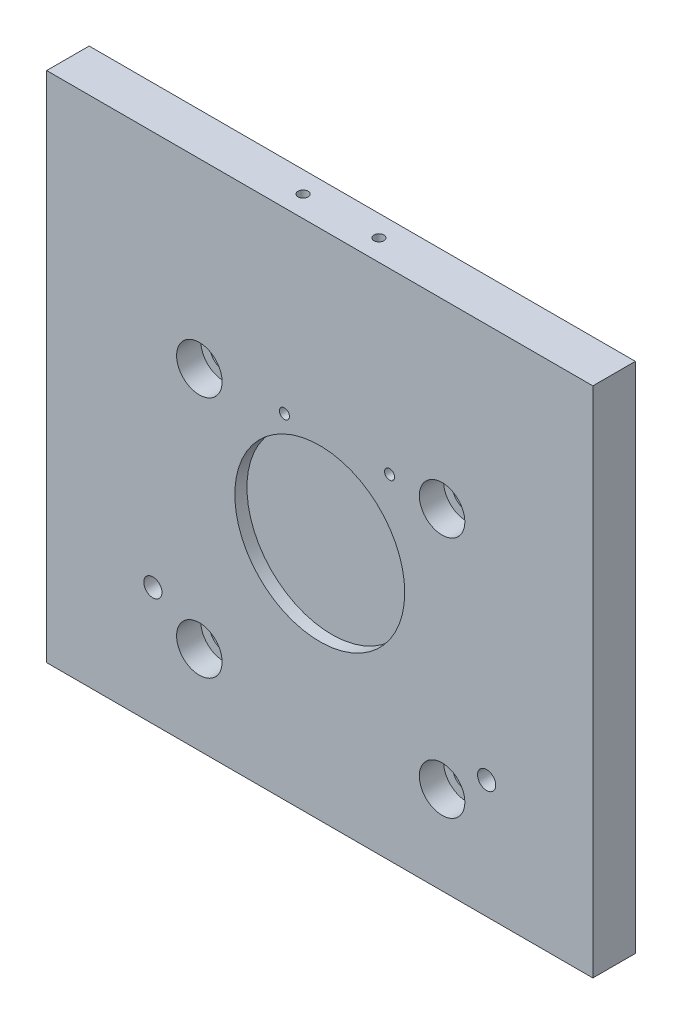
SolidWorks part; units mm, degrees
material "Polyetheretherketone (PEEK)"
ref_plane "Front Plane" through (0, 0, 0) normal (0, 0, 1) x (1, 0, 0)
ref_plane "Top Plane" through (0, 0, 0) normal (0, 1, 0) x (1, 0, 0)
ref_plane "Right Plane" through (0, 0, 0) normal (1, 0, 0) x (0, 0, -1)
ref_plane "Plane1" through (0, 0, 14) normal (0, 0, 1) x (1, 0, 0)
sketch "Sketch1" plane through (0, 0, 14) normal (0, 0, 1) x (1, 0, 0)
  line L0 (-90, -79) -> (90, -79)
  line L1 (90, -79) -> (90, 90)
  line L2 (90, 90) -> (-90, 90)
  line L3 (-90, 90) -> (-90, -79)
  dimension "D1" = 180
  dimension "D2" = 169
  dimension "D3" = 90
  dimension "D4" = 90
extrude "Boss-Extrude1" add sketch "Sketch1" against normal blind 14
hole_wizard "Ø6.0 (6) Diameter Hole1" positions "Sketch3" profile "Sketch2" hole size "Ø6.0" standard "ANSI Metric"
sketch "Sketch3" plane through (0, 0, 14) normal (0, 0, 1) x (1, 0, 0)
  point P0 (55, -40)
  point P1 (-55, -40)
  dimension "D1" = 55
  dimension "D2" = 40
  dimension "D3" = 55
  dimension "D4" = 40
sketch "Sketch2" plane through (55, -40, 14) normal (1, 0, 0) x (0, -1, 0)
  line L0 (0, 0) -> (0, 10)
  line L1 (0, 10) -> (3, 10)
  line L2 (3, 10) -> (3, 0)
  line L5 (3, 0) -> (0, 0)
  line L10 (0, 10) -> (-3, 10) construction
  line L11 (0, -6.35) -> (0, 107.95) construction
  dimension "Hole Dia." = 6
  dimension "Hole Depth" = 10
  dimension "Drill Angle" = 180
hole_wizard "M48 Clearance Hole1" positions "Sketch5" profile "Sketch4" hole size "M48" standard "ANSI Metric"
sketch "Sketch5" plane through (0, 0, 14) normal (0, 0, 1) x (1, 0, 0)
  point P0 (0, 0)
sketch "Sketch4" plane through (0, 0, 14) normal (1, 0, 0) x (0, -1, 0)
  line L0 (0, 0) -> (0, 4)
  line L1 (0, 4) -> (28, 4)
  line L2 (28, 4) -> (28, 0)
  line L5 (28, 0) -> (0, 0)
  line L10 (0, 4) -> (-28, 4) construction
  line L11 (0, -6.35) -> (0, 107.95) construction
  dimension "Hole Dia." = 56
  dimension "Hole Depth" = 4
  dimension "Drill Angle" = 180
hole_wizard "Ø3.3 (3.3) Diameter Hole1" positions "Sketch7" profile "Sketch6" hole size "Ø3.3" standard "ANSI Metric"
sketch "Sketch7" plane through (0, 0, 14) normal (0, 0, 1) x (1, 0, 0)
  point P0 (23, 31.25)
  point P1 (-11.64, 31.25)
  dimension "D1" = 23
  dimension "D2" = 31.25
  dimension "D3" = 11.64
  dimension "D4" = 31.25
sketch "Sketch6" plane through (23, 31.25, 14) normal (1, 0, 0) x (0, -1, 0)
  line L0 (0, 0) -> (0, 8)
  line L1 (0, 8) -> (1.65, 8)
  line L2 (1.65, 8) -> (1.65, 0)
  line L5 (1.65, 0) -> (0, 0)
  line L10 (0, 8) -> (-1.65, 8) construction
  line L11 (0, -6.35) -> (0, 107.95) construction
  dimension "Hole Dia." = 3.3
  dimension "Hole Depth" = 8
  dimension "Drill Angle" = 180
hole_wizard "CBORE for M8 Hex Head Bolt1" positions "Sketch9" profile "Sketch8" counterbore size "M8" standard "ANSI Metric"
sketch "Sketch9" plane through (0, 0, 14) normal (0, 0, 1) x (1, 0, 0)
  point P0 (40.316, 30.077)
  point P1 (-39.684, 30.077)
  point P2 (40.316, -49.923)
  point P3 (-39.684, -49.923)
  dimension "D1" = 40.316
  dimension "D2" = 30.077
  dimension "D3" = 39.684
  dimension "D4" = 30.077
  dimension "D5" = 40.316
  dimension "D6" = 49.923
  dimension "D7" = 39.684
  dimension "D8" = 49.923
sketch "Sketch8" plane through (40.316, 30.077, 14) normal (1, 0, 0) x (0, -1, 0)
  line L0 (0, 0) -> (0, 14)
  line L1 (0, 14) -> (4.5, 14)
  line L3 (4.5, 14) -> (4.5, 8)
  line L4 (4.5, 8) -> (7.5, 8)
  line L5 (7.5, 8) -> (7.5, 0)
  line L7 (7.5, 0) -> (0, 0)
  line L11 (0, -6.35) -> (0, 107.95) construction
  dimension "Thru Hole Dia." = 9
  dimension "Thru Hole Depth" = 14
  dimension "C'Bore Dia." = 15
  dimension "C'Bore Depth" = 8
hole_wizard "Ø3.3 (3.3) Diameter Hole2" positions "Sketch11" profile "Sketch10" hole size "Ø3.3" standard "ANSI Metric"
sketch "Sketch11" plane through (0, 90, 0) normal (0, 1, 0) x (1, 0, 0)
  point P0 (-12.5, -7)
  point P1 (12.5, -7)
  dimension "D1" = 12.5
  dimension "D2" = 7
  dimension "D3" = 12.5
  dimension "D4" = 7
sketch "Sketch10" plane through (-12.5, 90, 7) normal (1, 0, 0) x (0, 0, 1)
  line L0 (0, 0) -> (0, 10)
  line L1 (0, 10) -> (1.65, 10)
  line L2 (1.65, 10) -> (1.65, 0)
  line L5 (1.65, 0) -> (0, 0)
  line L10 (0, 10) -> (-1.65, 10) construction
  line L11 (0, -6.35) -> (0, 107.95) construction
  dimension "Hole Dia." = 3.3
  dimension "Hole Depth" = 10
  dimension "Drill Angle" = 180
